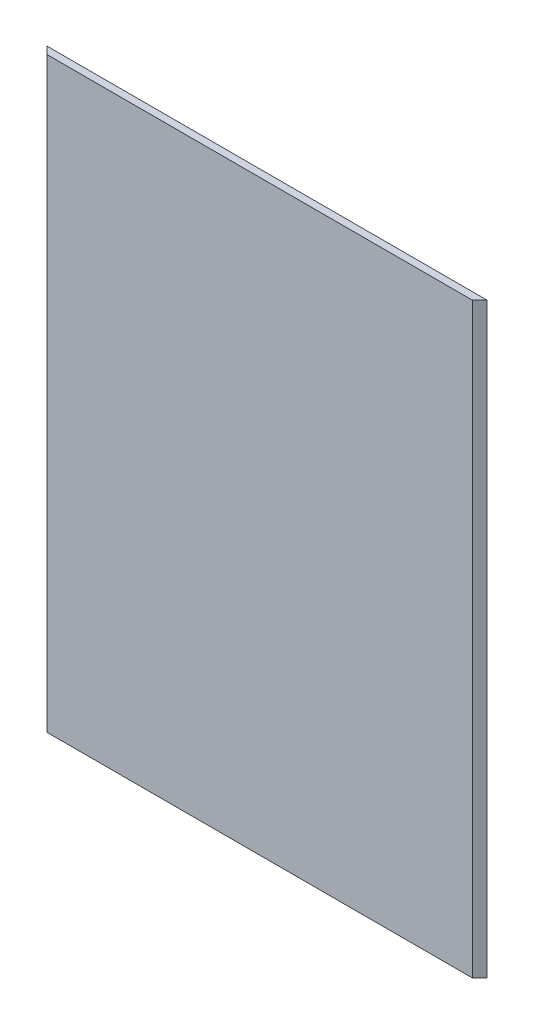
SolidWorks part; units mm, degrees
material "Verre"
ref_plane "Plan de face" through (0, 0, 0) normal (0, 0, 1) x (1, 0, 0)
ref_plane "Plan de dessus" through (0, 0, 0) normal (0, 1, 0) x (1, 0, 0)
ref_plane "Plan de droite" through (0, 0, 0) normal (1, 0, 0) x (0, 0, -1)
sketch "Esquisse1" plane through (0, 0, 0) normal (0, 0, 1) x (1, 0, 0)
  line L1 (150, -200) -> (-150, -200)
  line L2 (150, -200) -> (150, 200)
  line L3 (150, 200) -> (-150, 200)
  line L4 (-150, -200) -> (-150, 200)
  line L5 (150, -200) -> (-150, 200) construction
  line L6 (150, 200) -> (-150, -200) construction
  point P0 (0, 0)
  dimension "D1" = 300
  dimension "D2" = 400
extrude "Boss.-Extru.1" add sketch "Esquisse1" along normal blind 5
sketch "Esquisse2" plane through (0, 200, 0) normal (0, 1, 0) x (1, 0, 0)
  line L0 (-150, -5) -> (-150, 0)
  line L1 (-150, 0) -> (-145, -5)
  line L2 (150, -5) -> (-150, -5) construction
  line L3 (-145, -5) -> (-150, -5)
  line L4 (0, 0) -> (0, -5) construction
  line L5 (150, 0) -> (-150, 0) construction
  line L6 (145, -5) -> (150, -5)
  line L7 (150, 0) -> (145, -5)
  line L8 (150, -5) -> (150, 0)
extrude "Enlèv. mat.-Extru.1" cut sketch "Esquisse2" against normal through all
